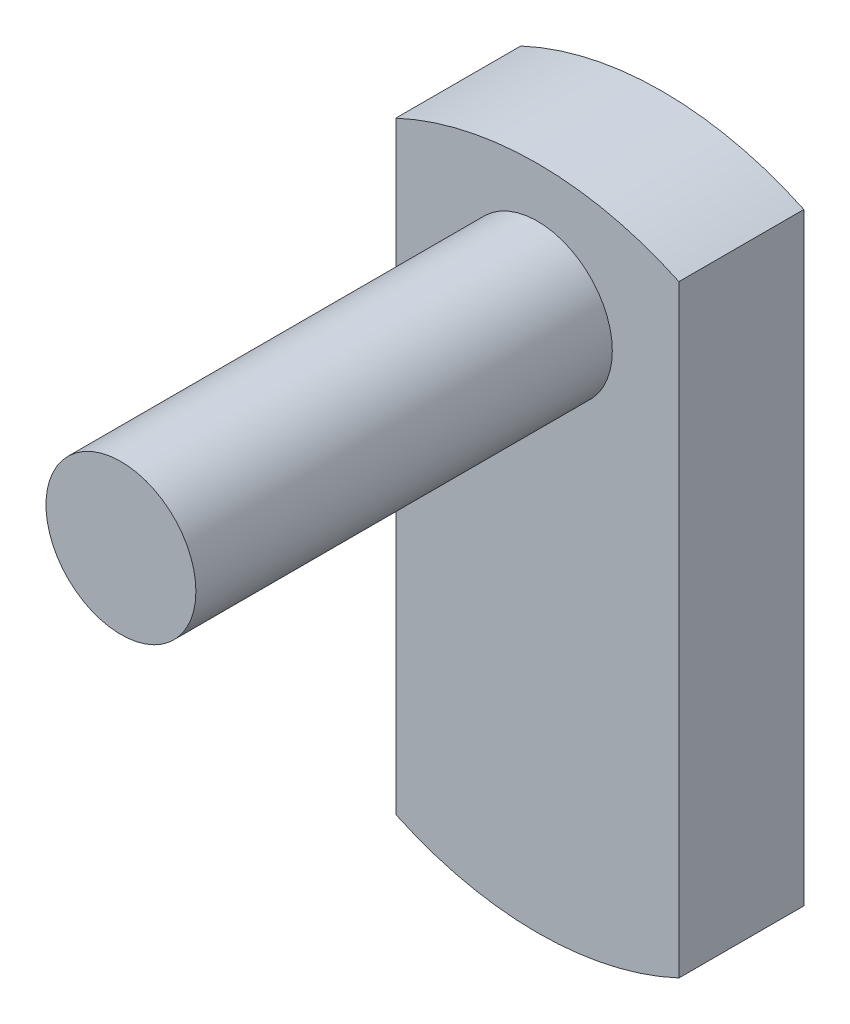
SolidWorks part; units mm, degrees
ref_plane "Alzado" through (0, 0, 0) normal (0, 0, 1) x (1, 0, 0)
ref_plane "Planta" through (0, 0, 0) normal (0, 1, 0) x (1, 0, 0)
ref_plane "Vista lateral" through (0, 0, 0) normal (1, 0, 0) x (0, 0, -1)
sketch "Croquis1" plane through (0, 0, 0) normal (0, 0, 1) x (1, 0, 0)
  circle A0 centre (0, 0) radius 40
  dimension "D3" = 80
extrude "Saliente-Extruir1" add sketch "Croquis1" along normal blind 15
sketch "Croquis3" plane through (0, 0, 15) normal (0, 0, 1) x (1, 0, 0)
  circle A0 centre (0, 25) radius 9
  dimension "D1" = 18
  dimension "D2" = 25
extrude "Saliente-Extruir2" add sketch "Croquis3" along normal blind 50
sketch "Croquis4" plane through (0, 0, 0) normal (0, 0, -1) x (-1, 0, 0)
  line L1 (-15, 0) -> (15, 0)
  line L2 (-15, 0) -> (-15, -30)
  line L3 (-15, -30) -> (15, -30)
  line L4 (15, 0) -> (15, -30)
  circle A1 centre (0, 0) radius 40 construction
  dimension "D1" = 30
  dimension "D2" = 30
  dimension "D3" = 0
extrude "Cortar-Extruir1" cut sketch "Croquis4" against normal blind 10
sketch "Croquis5" plane through (0, 0, 15) normal (0, 0, 1) x (1, 0, 0)
  line L0 (-31.225, 25) -> (31.225, 25) construction
  line L1 (-17, 36.2077) -> (-17, -36.2077)
  line L2 (17, 36.2077) -> (17, -36.2077)
  line L3 (0, 34) -> (0, 16) construction
  circle A0 centre (0, 0) radius 40 construction
  circle A1 centre (0, 25) radius 9 construction
  circle A2 centre (0, 25) radius 9 construction
  arc A3 (17, -36.2077) -> (17, 36.2077) centre (0, 0) ccw
  arc A4 (-17, 36.2077) -> (-17, -36.2077) centre (0, 0) ccw
  dimension "D1" = 17
  dimension "D2" = 17
extrude "Cortar-Extruir3" cut sketch "Croquis5" against normal through all
